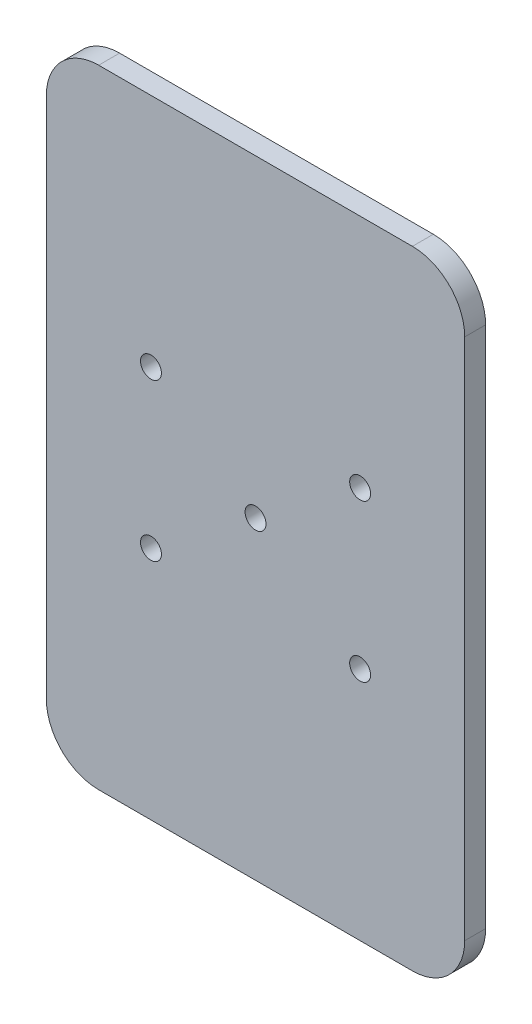
SolidWorks part; units mm, degrees
ref_plane "Front Plane" through (0, 0, 0) normal (0, 0, 1) x (1, 0, 0)
ref_plane "Top Plane" through (0, 0, 0) normal (0, 1, 0) x (1, 0, 0)
ref_plane "Right Plane" through (0, 0, 0) normal (1, 0, 0) x (0, 0, -1)
sketch "Sketch1" plane through (0, 0, 0) normal (0, 0, 1) x (1, 0, 0)
  line L1 (-65.9851, 26.8064) -> (-25.9851, 26.8064)
  line L2 (-65.9851, 26.8064) -> (-65.9851, -33.1936)
  line L3 (-65.9851, -33.1936) -> (-25.9851, -33.1936)
  line L4 (-25.9851, 26.8064) -> (-25.9851, -33.1936)
  dimension "D1" = 40
  dimension "D2" = 60
extrude "Boss-Extrude4" add sketch "Sketch1" against normal blind 2 contours L2 L3 L4 L1
fillet "Fillet1" radius 5 4 edges at (-25.9851, 26.8064, -1) (-25.9851, -33.1936, -1) (-65.9851, -33.1936, -1) (-65.9851, 26.8064, -1)
sketch "Sketch12" plane through (0, 0, -2) normal (0, 0, -1) x (-1, 0, 0)
  line L0 (65.9851, 21.8064) -> (65.9851, -28.1936) construction
  line L1 (60.9851, 26.8064) -> (30.9851, 26.8064) construction
  circle A0 centre (45.9851, -3.1936) radius 1
  dimension "D1" = 2
  dimension "D2" = 20
  dimension "D3" = 30
extrude "Cut-Extrude6" cut sketch "Sketch12" against normal blind 12 contours A0
sketch "Sketch13" plane through (0, 0, -2) normal (0, 0, -1) x (-1, 0, 0)
  line L0 (65.9851, 21.8064) -> (65.9851, -28.1936) construction
  line L1 (60.9851, 26.8064) -> (30.9851, 26.8064) construction
  line L2 (60.9851, -33.1936) -> (30.9851, -33.1936) construction
  circle A0 centre (55.9851, 4.3064) radius 1
  circle A1 centre (55.9851, -10.6936) radius 1
  dimension "D1" = 10
  dimension "D2" = 22.5
  dimension "D3" = 22.5
  dimension "D4" = 10
extrude "Cut-Extrude7" cut sketch "Sketch13" against normal blind 10 and the other way blind 8
sketch "Sketch14" plane through (0, 0, 0) normal (0, 0, 1) x (1, 0, 0)
  line L0 (-60.9851, 26.8064) -> (-30.9851, 26.8064) construction
  line L1 (-60.9851, -33.1936) -> (-30.9851, -33.1936) construction
  line L2 (-25.9851, 21.8064) -> (-25.9851, -28.1936) construction
  circle A0 centre (-35.9851, 4.3064) radius 1
  circle A1 centre (-35.9851, -10.6936) radius 1
  dimension "D1" = 22.5
  dimension "D2" = 22.5
  dimension "D3" = 10
  dimension "D4" = 10
extrude "Cut-Extrude8" cut sketch "Sketch14" against normal blind 10
